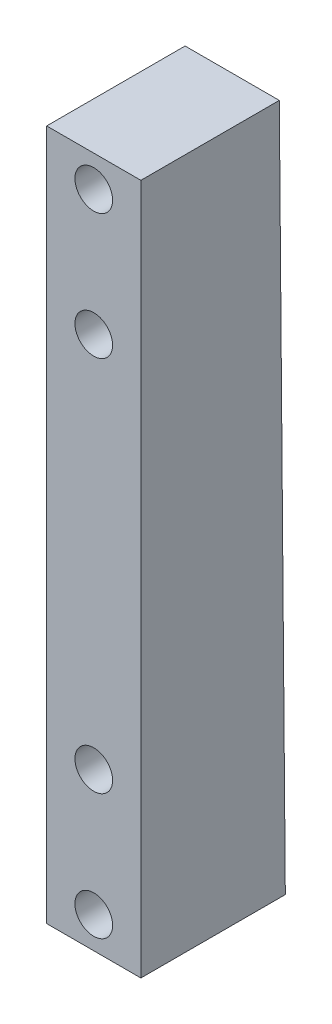
SolidWorks part; units mm, degrees
ref_plane "Front" through (0, 0, 0) normal (0, 0, 1) x (1, 0, 0)
ref_plane "Top" through (0, 0, 0) normal (0, 1, 0) x (1, 0, 0)
ref_plane "Right" through (0, 0, 0) normal (1, 0, 0) x (0, 0, -1)
ref_plane "Plane1" through (-7.5, 0, 0) normal (-1, 0, 0) x (0, -1, 0)
sketch "Sketch1" plane through (-7.5, 0, 0) normal (-1, 0, 0) x (0, -1, 0)
  line L0 (-55, 0) -> (-55, -23)
  line L1 (-55, -23) -> (55, -23)
  line L2 (55, -23) -> (55, 0)
  line L3 (55, 0) -> (-55, 0)
  dimension "D1" = 23
  dimension "D2" = 110
extrude "Boss-Extrude1" add sketch "Sketch1" against normal blind 15
hole_wizard "Ø6.0 (6) Diameter Hole1" positions "Sketch3" profile "Sketch2" hole size "Ø6.0" standard "ANSI Metric"
sketch "Sketch3" plane through (0, 0, 0) normal (0, 0, 1) x (1, 0, 0)
  line L0 (0, 30) -> (0, -30) construction
  point P0 (0, 30)
  point P1 (0, -30)
  dimension "D1" = 60
sketch "Sketch2" plane through (0, 30, 0) normal (1, 0, 0) x (0, -1, 0)
  line L0 (0, 0) -> (0, 7.8126)
  line L1 (0, 7.8126) -> (3, 6.01)
  line L2 (3, 6.01) -> (3, 0)
  line L5 (3, 0) -> (0, 0)
  line L10 (0, 7.8126) -> (-3, 6.01) construction
  line L11 (0, -6.35) -> (0, 107.95) construction
  dimension "Hole Dia." = 6
  dimension "Hole Depth" = 6.01
  dimension "Drill Angle" = 118
hole_wizard "CSK for M3.5 Flat Head Machine Screw1" positions "Sketch5" profile "Sketch4" countersink size "M3.5" standard "ANSI Metric"
sketch "Sketch5" plane through (0, 0, 0) normal (0, 0, 1) x (1, 0, 0)
  line L0 (0, -50) -> (0, 50) construction
  point P0 (0, 50)
  point P1 (0, -50)
  dimension "D1" = 100
sketch "Sketch4" plane through (0, 50, 0) normal (1, 0, 0) x (0, -1, 0)
  line L0 (0, 0) -> (0, 23)
  line L1 (0, 23) -> (2.1, 23)
  line L2 (2.1, 23) -> (2.1, 6.5408)
  line L3 (2.1, 6.5408) -> (3, 6)
  line L4 (3, 6) -> (3, 0)
  line L6 (3, 0) -> (0, 0)
  line L7 (-2.1, 6.5408) -> (-3, 6) construction
  line L11 (0, -6.35) -> (0, 107.95) construction
  dimension "Thru Hole Dia." = 4.2
  dimension "Thru Hole Depth" = 23
  dimension "C'Sink Dia." = 6
  dimension "C'Sink Angle" = 118
  dimension "Head Clearance" = 6
sketch "Sketch6" plane through (7.5, 0, 0) normal (1, 0, 0) x (0, 0, -1)
  line L0 (23, -55) -> (22.04, 55)
  line L1 (0, 55) -> (23, 55) construction
  line L2 (22.04, 55) -> (23, 55)
  line L3 (23, 55) -> (23, -55)
  dimension "D1" = 0.5
extrude "Cut-Extrude1" cut sketch "Sketch6" against normal through all
